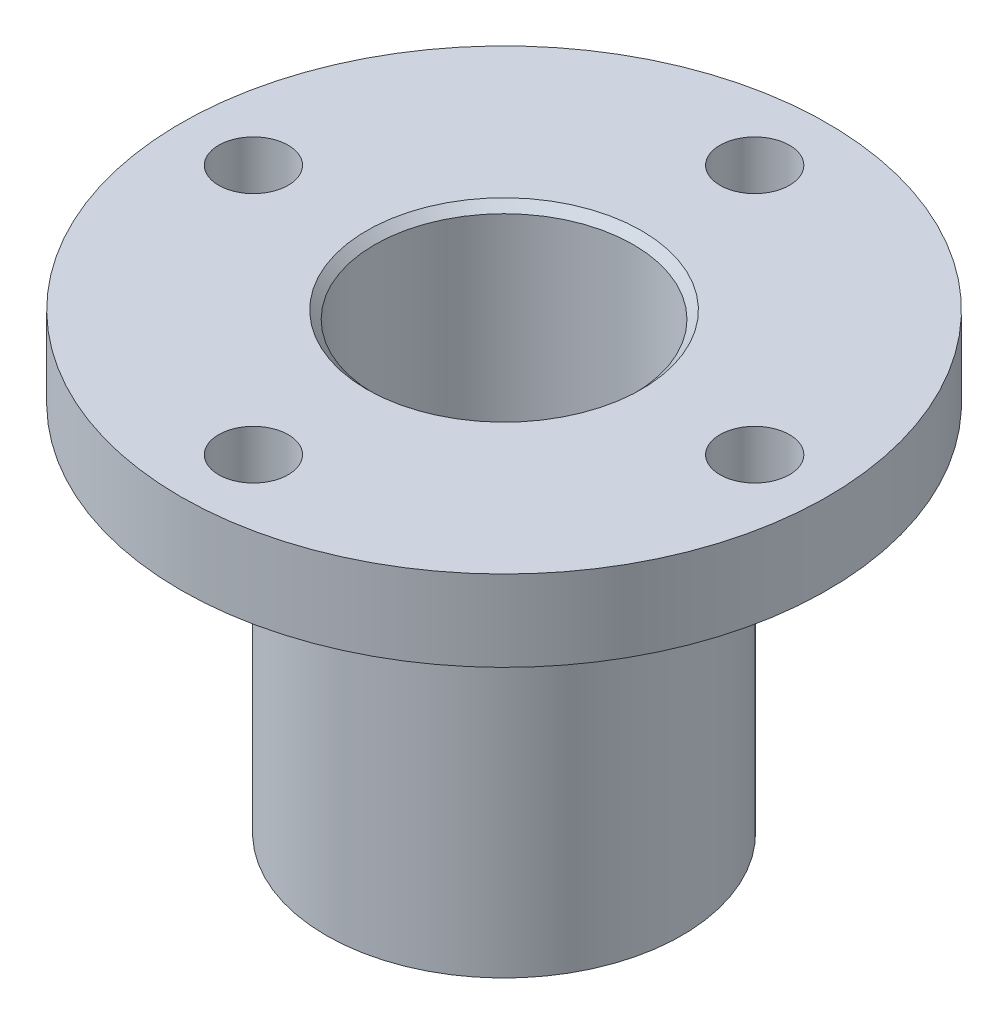
SolidWorks part; units mm, degrees
ref_plane "Front" through (0, 0, 0) normal (0, 0, 1) x (1, 0, 0)
ref_plane "Top" through (0, 0, 0) normal (0, 1, 0) x (1, 0, 0)
ref_plane "Right" through (0, 0, 0) normal (1, 0, 0) x (0, 0, -1)
sketch "草图1" plane through (0, 0, 0) normal (0, 1, 0) x (1, 0, 0)
  circle A0 centre (0, 0) radius 11
  dimension "D1" = 22
extrude "凸台-拉伸1" add sketch "草图1" along normal blind 23
sketch "草图2" plane through (0, 23, 0) normal (0, 1, 0) x (1, 0, 0)
  circle A0 centre (0, 0) radius 20
  dimension "D1" = 40
extrude "凸台-拉伸2" add sketch "草图2" along normal blind 5
sketch "草图3" plane through (0, 28, 0) normal (0, 1, 0) x (1, 0, 0)
  circle A0 centre (0, 0) radius 8
  dimension "D1" = 16
extrude "切除-拉伸1" cut sketch "草图3" against normal through all
chamfer "倒角1" distance 0.5 angle 45 2 edges at (0, 0, 8) (0, 28, 8)
sketch "草图4" plane through (0, 28, 0) normal (0, 1, 0) x (1, 0, 0)
  circle A0 centre (0, 15.5) radius 2.15
  circle A1 centre (0, 0) radius 15.5 construction
  circle A2 centre (15.5, 0) radius 2.15
  circle A3 centre (0, -15.5) radius 2.15
  circle A4 centre (-15.5, 0) radius 2.15
  point P14 (0, 0)
  dimension "D1" = 4.3
  dimension "D2" = 31
  dimension "D3" = 4
extrude "切除-拉伸2" cut sketch "草图4" against normal through all
